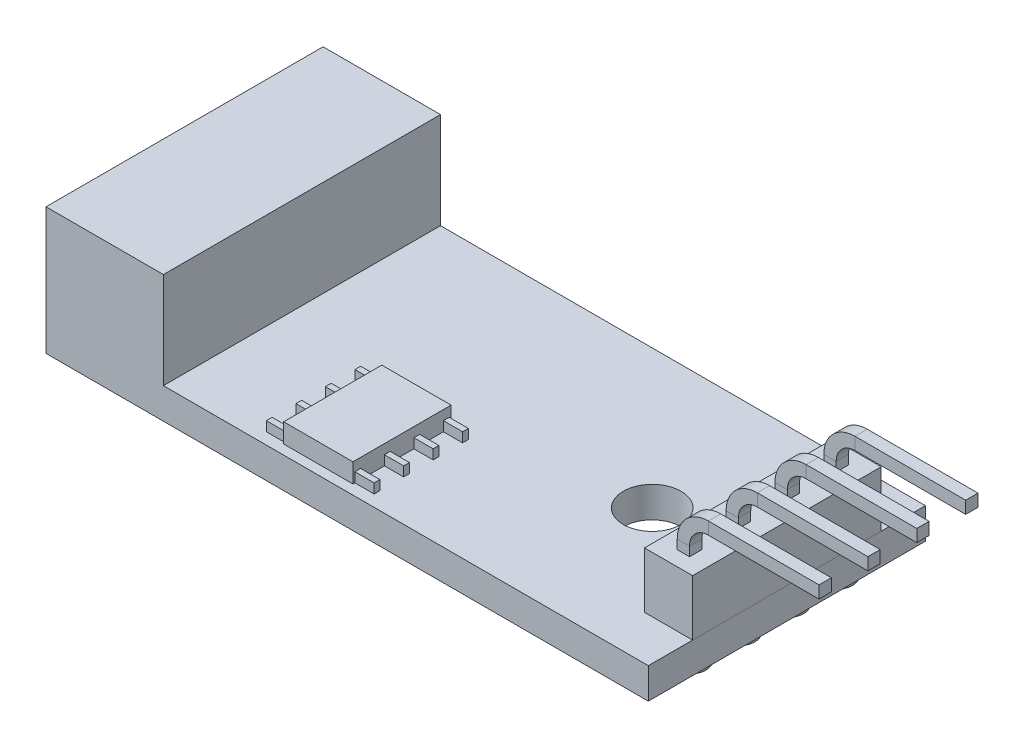
SolidWorks part; units mm, degrees
other "LM393"
other "A0"
other "D0"
other "GND"
other "PCB"
ref_plane "Alzado" through (0, 0, 0) normal (0, 0, 1) x (1, 0, 0)
ref_plane "Planta" through (0, 0, 0) normal (0, 1, 0) x (1, 0, 0)
ref_plane "Vista lateral" through (0, 0, 0) normal (1, 0, 0) x (0, 0, -1)
sketch "Croquis1" plane through (0, 0, 0) normal (0, 1, 0) x (1, 0, 0)
  line L1 (-15.65, -7.2) -> (15.65, -7.2)
  line L2 (-15.65, -7.2) -> (-15.65, 7.2)
  line L3 (-15.65, 7.2) -> (15.65, 7.2)
  line L4 (15.65, -7.2) -> (15.65, 7.2)
  line L5 (-15.65, -7.2) -> (15.65, 7.2) construction
  line L6 (-15.65, 7.2) -> (15.65, -7.2) construction
  circle A0 centre (8.65, 0) radius 1.5
  point P0 (0, 0)
  dimension "D3" = 3
  dimension "D4" = 5.5
  dimension "D1" = 31.3
  dimension "D2" = 14.4
extrude "BASE" add sketch "Croquis1" along normal blind 1.6
sketch "Croquis2" plane through (0, 1.6, 0) normal (0, 1, 0) x (1, 0, 0)
  line L0 (15.65, -7.2) -> (15.65, 7.2) construction
  line L1 (13.15, -4.9) -> (15.65, -4.9)
  line L2 (13.15, -4.9) -> (13.15, 4.9)
  line L3 (13.15, 4.9) -> (15.65, 4.9)
  line L4 (15.65, -4.9) -> (15.65, 4.9)
  line L5 (13.15, -4.9) -> (15.65, 4.9) construction
  line L6 (13.15, 4.9) -> (15.65, -4.9) construction
  line L7 (14.4, 3.81) -> (14.4, 1.27) construction
  line L8 (14.4, 1.27) -> (14.4, -1.27) construction
  line L9 (14.4, -1.27) -> (14.4, -3.81) construction
  point P0 (14.4, 0)
  point P7 (14.4, 3.81)
  point P9 (14.4, 1.27)
  point P10 (14.4, -1.27)
  point P11 (14.4, -3.81)
  point P14 (14.4, 0)
  dimension "D1" = 2.5
  dimension "D2" = 9.8
  dimension "D3" = 2.54
extrude "BASE PINES" add sketch "Croquis2" along normal blind 2.9 separate body
ref_plane "PLANO PIN Vcc" through (0, 0, -3.81) normal (0, 0, 1) x (1, 0, 0)
sketch "DIRECTRIZ" plane through (0, 0, -3.81) normal (0, 0, 1) x (1, 0, 0)
  line L0 (14.4, 4.5) -> (14.4, 4.98)
  line L1 (13.15, 4.5) -> (15.65, 4.5) construction
  line L2 (15.7, 6.28) -> (21.45, 6.28)
  line L3 (13.15, 4.5) -> (13.15, 1.6) construction
  line L4 (21.45, 6.6) -> (21.45, 5.96) construction
  line L5 (-15.65, 0) -> (15.65, 0) construction
  arc A0 (14.4, 4.98) -> (15.7, 6.28) centre (15.7, 4.98) cw
  point P11 (21.45, 6.28)
  dimension "D4" = 1.3
  dimension "D1" = 8.3
  dimension "D2" = 0.64
  dimension "D3" = 6.6
sketch "SECCION" plane through (0, 4.5, 0) normal (0, 1, 0) x (1, 0, 0)
  line L1 (14.08, 4.13) -> (14.72, 4.13)
  line L2 (14.08, 4.13) -> (14.08, 3.49)
  line L3 (14.08, 3.49) -> (14.72, 3.49)
  line L4 (14.72, 4.13) -> (14.72, 3.49)
  line L5 (14.08, 4.13) -> (14.72, 3.49) construction
  line L6 (14.08, 3.49) -> (14.72, 4.13) construction
  point P0 (14.4, 3.81)
  dimension "D1" = 0.64
  dimension "D2" = 0.64
sweep "PIN Vcc" add profiles "SECCION" path "DIRECTRIZ"
pattern_linear "MatrizL1" count 4 spacing 2.54 along (0, 0, 1) of bodies 103
sketch "Croquis5" plane through (0, 1.6, 0) normal (0, 1, 0) x (1, 0, 0)
  line L0 (-15.65, -7.2) -> (15.65, -7.2) construction
  line L1 (-15.65, 7.2) -> (-9.55, 7.2)
  line L2 (-15.65, 7.2) -> (-15.65, -7.2)
  line L3 (-15.65, -7.2) -> (-9.55, -7.2)
  line L4 (-9.55, 7.2) -> (-9.55, -7.2)
  dimension "D1" = 6.1
sketch "Croquis7" plane through (0, 1.6, 0) normal (0, 1, 0) x (1, 0, 0)
  line L0 (-15.65, -7.2) -> (15.65, -7.2) construction
  line L1 (-3.8, -1.6) -> (-0.2, -1.6)
  line L2 (-3.8, -1.6) -> (-3.8, -6.7)
  line L3 (-3.8, -6.7) -> (-0.2, -6.7)
  line L4 (-0.2, -1.6) -> (-0.2, -6.7)
  line L5 (-3.8, -1.6) -> (-0.2, -6.7) construction
  line L6 (-3.8, -6.7) -> (-0.2, -1.6) construction
  point P0 (-2, -4.15)
  dimension "D1" = 2
  dimension "D2" = 0.5
  dimension "D3" = 3.6
  dimension "D4" = 5.1
extrude "Saliente-Extruir4" add sketch "Croquis7" along normal blind 1 separate body
sketch "Croquis8" plane through (0, 1.6, 0) normal (0, 1, 0) x (1, 0, 0)
  line L0 (-3.8, -1.6) -> (-3.8, -6.7) construction
  line L1 (-4.8, -1.7) -> (-3.8, -1.7)
  line L2 (-4.8, -1.7) -> (-4.8, -2)
  line L3 (-4.8, -2) -> (-3.8, -2)
  line L4 (-3.8, -1.7) -> (-3.8, -2)
  line L5 (-0.2, -6.7) -> (-0.2, -1.6) construction
  line L6 (-4.8, -3.2333) -> (-3.8, -3.2333)
  line L7 (-4.8, -3.2333) -> (-4.8, -3.5333)
  line L8 (-4.8, -3.5333) -> (-3.8, -3.5333)
  line L9 (-3.8, -3.2333) -> (-3.8, -3.5333)
  line L10 (-4.8, -4.7667) -> (-3.8, -4.7667)
  line L11 (-4.8, -4.7667) -> (-4.8, -5.0667)
  line L12 (-4.8, -5.0667) -> (-3.8, -5.0667)
  line L13 (-3.8, -4.7667) -> (-3.8, -5.0667)
  line L14 (-4.8, -6.3) -> (-3.8, -6.3)
  line L15 (-4.8, -6.3) -> (-4.8, -6.6)
  line L16 (-4.8, -6.6) -> (-3.8, -6.6)
  line L17 (-3.8, -6.3) -> (-3.8, -6.6)
  line L18 (0.8, -1.7) -> (-0.2, -1.7)
  line L19 (0.8, -1.7) -> (0.8, -2)
  line L20 (0.8, -2) -> (-0.2, -2)
  line L21 (-0.2, -1.7) -> (-0.2, -2)
  line L22 (-0.2, -1.6) -> (-3.8, -1.6) construction
  line L23 (0.8, -3.2333) -> (-0.2, -3.2333)
  line L24 (0.8, -3.2333) -> (0.8, -3.5333)
  line L25 (0.8, -3.5333) -> (-0.2, -3.5333)
  line L26 (-0.2, -3.2333) -> (-0.2, -3.5333)
  line L27 (0.8, -4.7667) -> (-0.2, -4.7667)
  line L28 (0.8, -4.7667) -> (0.8, -5.0667)
  line L29 (0.8, -5.0667) -> (-0.2, -5.0667)
  line L30 (-0.2, -4.7667) -> (-0.2, -5.0667)
  line L31 (0.8, -6.3) -> (-0.2, -6.3)
  line L32 (0.8, -6.3) -> (0.8, -6.6)
  line L33 (0.8, -6.6) -> (-0.2, -6.6)
  line L34 (-0.2, -6.3) -> (-0.2, -6.6)
  line L35 (-4.8, -2) -> (-4.8, -3.2333) construction
  line L36 (-4.8, -3.5333) -> (-4.8, -4.7667) construction
  line L37 (-4.8, -5.0667) -> (-4.8, -6.3) construction
  line L38 (-3.8, -6.7) -> (-0.2, -6.7) construction
  dimension "D1" = 0.1
  dimension "D2" = 0.3
  dimension "D3" = 1
  dimension "D4" = 0.1
extrude "Saliente-Extruir5" add sketch "Croquis8" along normal blind 0.5
sketch "Croquis9" plane through (0, 0, 0) normal (0, -1, 0) x (1, 0, 0)
  line L0 (-10.575, 5.15) -> (-13.15, 5.15) construction
  line L1 (-13.15, 5.15) -> (-13.15, 2.575) construction
  line L2 (-13.15, 2.575) -> (-13.15, 0) construction
  line L3 (-13.15, 0) -> (-13.15, -2.575) construction
  line L4 (-13.15, -2.575) -> (-13.15, -5.15) construction
  line L5 (-13.15, -5.15) -> (-10.575, -5.15) construction
  line L6 (-10.575, -5.15) -> (-10.575, -2.575) construction
  line L7 (-10.575, 5.15) -> (-10.575, 2.575) construction
  line L8 (-15.65, -7.2) -> (-15.65, 7.2) construction
  circle A0 centre (-13.15, 5.15) radius 0.85
  circle A1 centre (-10.575, 5.15) radius 0.85
  circle A2 centre (-10.575, 2.575) radius 0.85
  circle A3 centre (-13.15, 2.575) radius 0.85
  circle A4 centre (-13.15, 0) radius 0.85
  circle A5 centre (-13.15, -2.575) radius 0.85
  circle A6 centre (-13.15, -5.15) radius 0.85
  circle A7 centre (-10.575, -5.15) radius 0.85
  circle A8 centre (-10.575, -2.575) radius 0.85
  circle A9 centre (14.4, 3.81) radius 0.85
  circle A10 centre (14.4, 1.27) radius 0.85
  circle A11 centre (14.4, -1.27) radius 0.85
  circle A12 centre (14.4, -3.81) radius 0.85
  dimension "D1" = 1.7
  dimension "D2" = 12
  dimension "D3" = 2.5
extrude "Saliente-Extruir6" add sketch "Croquis9" along normal blind 0.5
extrude "Boss-Extrude1" add sketch "Croquis5" along normal blind 5
